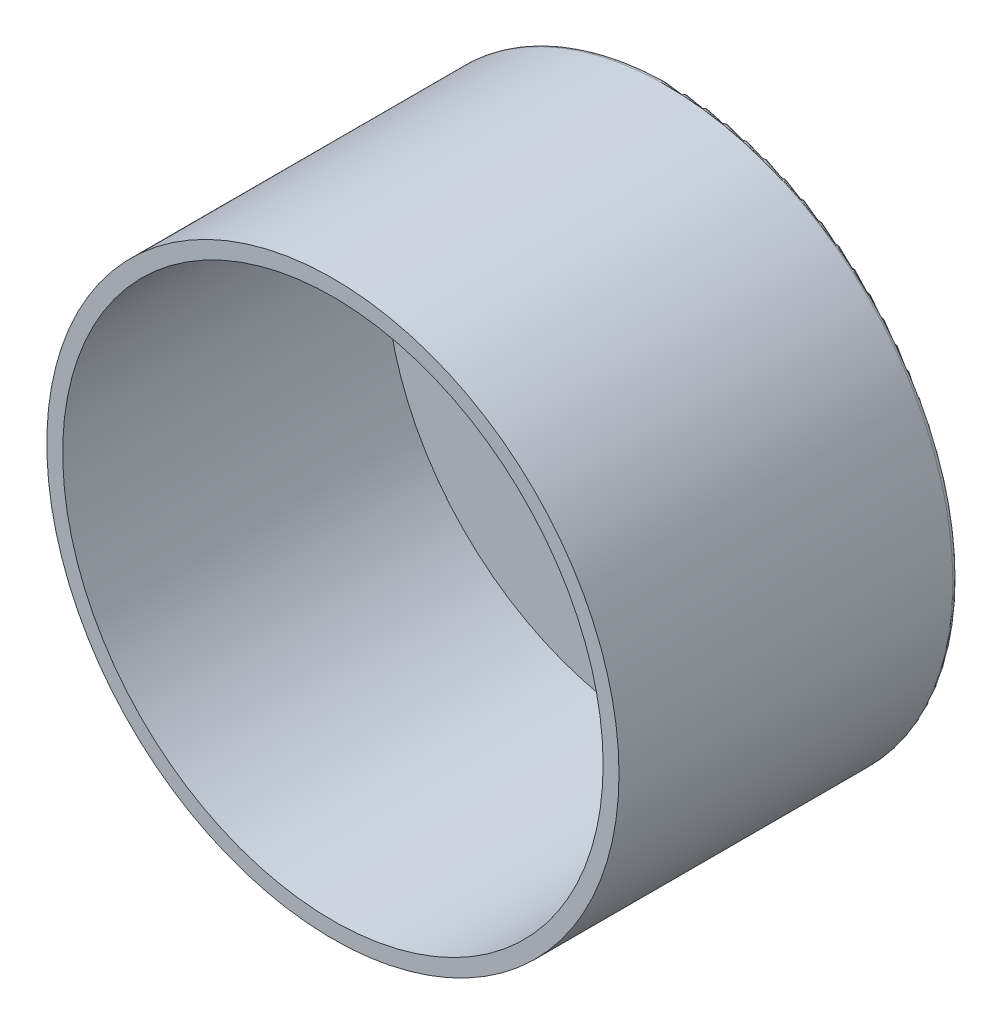
SolidWorks part; units mm, degrees
ref_plane "Front Plane" through (0, 0, 0) normal (0, 0, 1) x (1, 0, 0)
ref_plane "Top Plane" through (0, 0, 0) normal (0, 1, 0) x (1, 0, 0)
ref_plane "Right Plane" through (0, 0, 0) normal (1, 0, 0) x (0, 0, -1)
sketch "Sketch1" plane through (0, 0, 0) normal (0, 0, 1) x (1, 0, 0)
  circle A0 centre (0, 0) radius 27
  dimension "D1" = 54
extrude "Boss-Extrude1" add sketch "Sketch1" along normal blind 32
shell "Shell3" thickness 1.5
fillet "Fillet1" radius 0.5 1 edges at (27, 0, 0)
